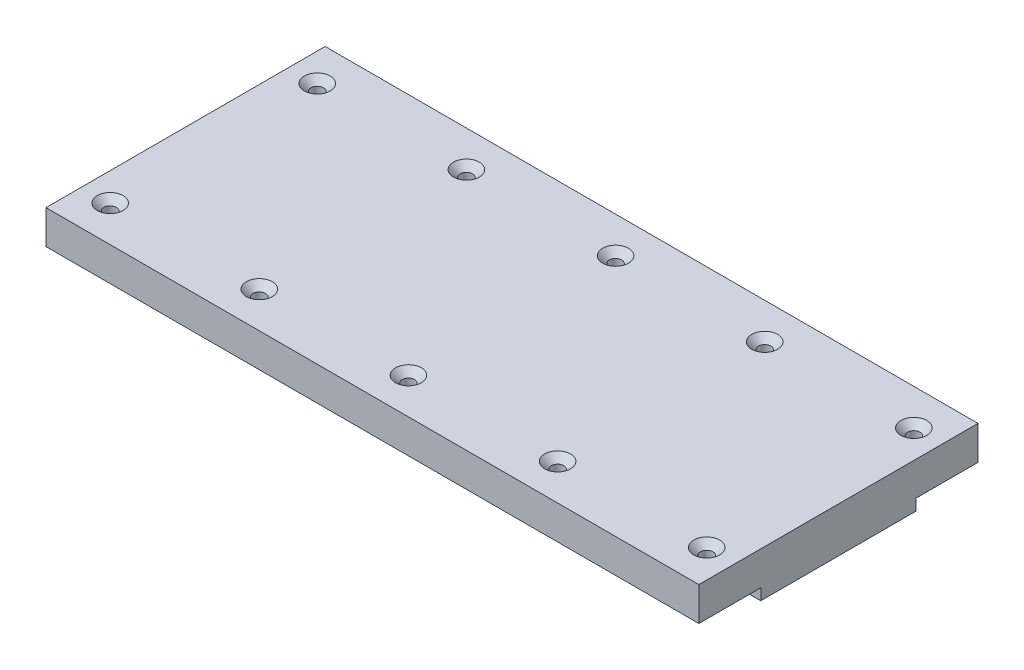
SolidWorks part; units mm, degrees
ref_plane "Alzado" through (0, 0, 0) normal (0, 0, 1) x (1, 0, 0)
ref_plane "Planta" through (0, 0, 0) normal (0, 1, 0) x (1, 0, 0)
ref_plane "Vista lateral" through (0, 0, 0) normal (1, 0, 0) x (0, 0, -1)
sketch "Croquis1" plane through (0, 0, 0) normal (0, 1, 0) x (1, 0, 0)
  line L1 (-290, -69) -> (290, -69)
  line L2 (-290, -69) -> (-290, 69)
  line L3 (-290, 69) -> (290, 69)
  line L4 (290, -69) -> (290, 69)
  line L5 (-290, -69) -> (290, 69) construction
  line L6 (-290, 69) -> (290, -69) construction
  point P0 (0, 0)
  dimension "D1" = 580
  dimension "D2" = 138
extrude "Saliente-Extruir1" add sketch "Croquis1" along normal blind 10
sketch "Croquis2" plane through (0, 10, 0) normal (0, 1, 0) x (1, 0, 0)
  line L1 (-290, -124) -> (290, -124)
  line L2 (-290, -124) -> (-290, 124)
  line L3 (-290, 124) -> (290, 124)
  line L4 (290, -124) -> (290, 124)
  line L5 (-290, -124) -> (290, 124) construction
  line L6 (-290, 124) -> (290, -124) construction
  point P0 (0, 0)
  dimension "D1" = 580
  dimension "D2" = 248
extrude "Saliente-Extruir2" add sketch "Croquis2" along normal blind 30
sketch "Croquis3" plane through (0, 40, 0) normal (0, 1, 0) x (1, 0, 0)
  line L0 (-290, 0) -> (290, 0) construction
  line L1 (290, -124) -> (290, 124) construction
  line L2 (-265, 92) -> (-265, -92) construction
  line L3 (-290, 124) -> (-290, -124) construction
  circle A0 centre (-265, 92) radius 5.5
  circle A1 centre (-132.5, 92) radius 5.5
  circle A2 centre (0, 92) radius 5.5
  circle A3 centre (132.5, 92) radius 5.5
  circle A4 centre (265, 92) radius 5.5
  circle A5 centre (-265, -92) radius 5.5
  circle A6 centre (-132.5, -92) radius 5.5
  circle A7 centre (0, -92) radius 5.5
  circle A8 centre (132.5, -92) radius 5.5
  circle A9 centre (265, -92) radius 5.5
  point P20 (-265, 0)
  point P26 (0, 0)
  point P30 (0, 0)
  dimension "D1" = 11
  dimension "D2" = 184
  dimension "D3" = 25
  dimension "D4" = 132.5
  dimension "D5" = 132.5
  dimension "D6" = 132.5
  dimension "D7" = 132.5
extrude "Cortar-Extruir1" cut sketch "Croquis3" against normal through all
chamfer "Chaflán1" distance 6 angle 45 10 edges at (-265, 40, 97.5) (-132.5, 40, 97.5) (0, 40, 97.5) (132.5, 40, 97.5) (265, 40, 97.5) (265, 40, -86.5) (132.5, 40, -86.5) (0, 40, -86.5) (-132.5, 40, -86.5) (-265, 40, -86.5)
